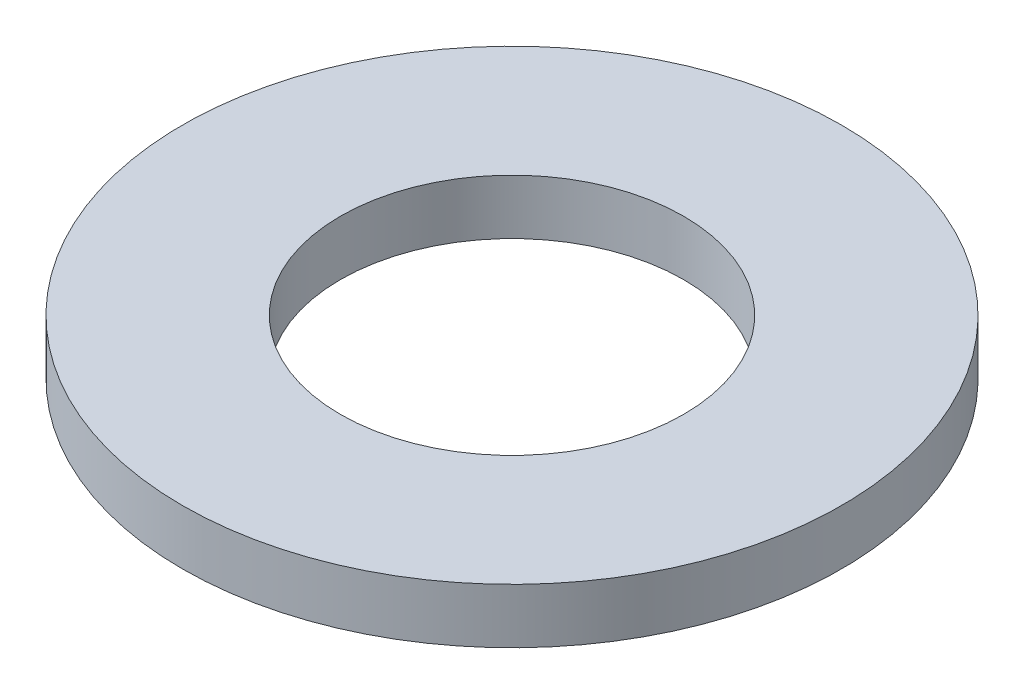
SolidWorks part; units mm, degrees
ref_plane "Front Plane" through (0, 0, 0) normal (0, 0, 1) x (1, 0, 0)
ref_plane "Top Plane" through (0, 0, 0) normal (0, 1, 0) x (1, 0, 0)
ref_plane "Right Plane" through (0, 0, 0) normal (1, 0, 0) x (0, 0, -1)
sketch "Sketch1" plane through (0, 0, 0) normal (0, 1, 0) x (1, 0, 0)
  circle A0 centre (0, 0) radius 3.125
  circle A1 centre (0, 0) radius 6
  dimension "D1" = 6.25
  dimension "D2" = 12
extrude "Boss-Extrude1" add sketch "Sketch1" along normal blind 1
